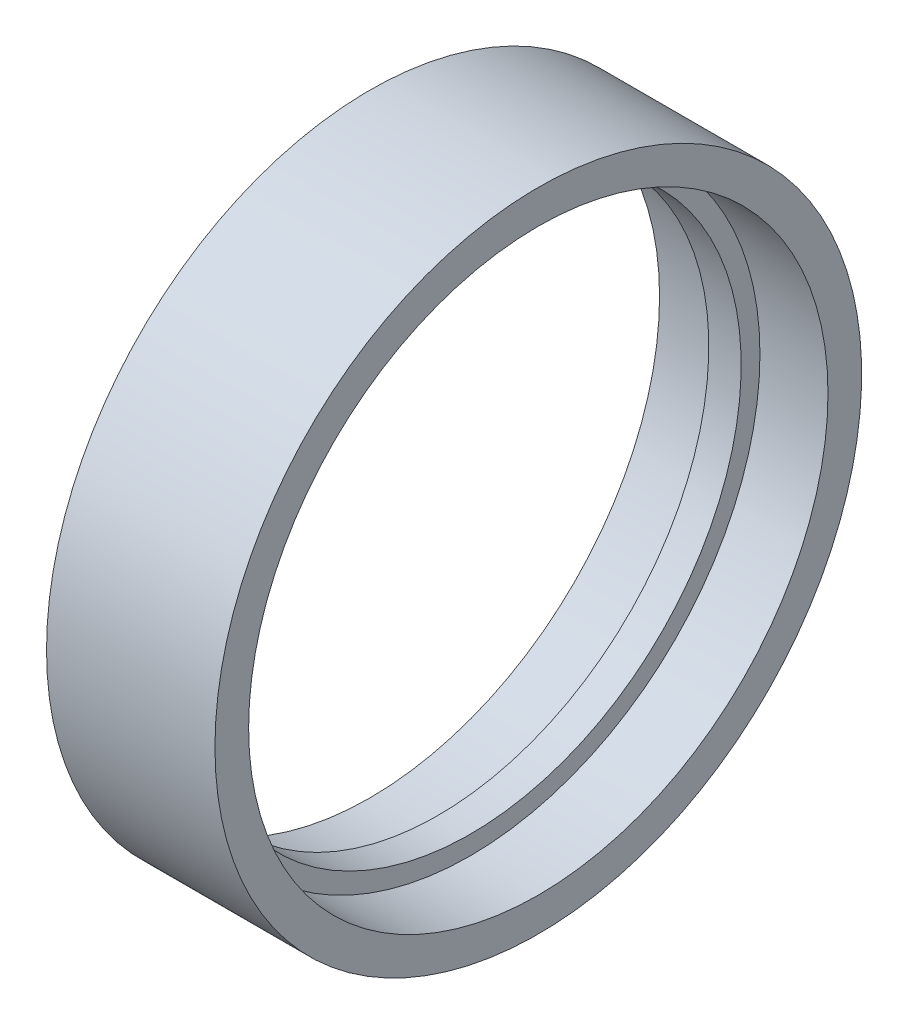
SolidWorks part; units mm, degrees
ref_plane "Ebene vorne" through (0, 0, 0) normal (0, 0, 1) x (1, 0, 0)
ref_plane "Ebene oben" through (0, 0, 0) normal (0, 1, 0) x (1, 0, 0)
ref_plane "Ebene rechts" through (0, 0, 0) normal (1, 0, 0) x (0, 0, -1)
sketch "Skizze1" plane through (0, 0, 0) normal (0, 0, 1) x (1, 0, 0)
  line L0 (-14.8859, 0) -> (39.3957, 0) construction
  line L1 (-12.5, 48) -> (12.5, 48)
  line L2 (-12.5, 48) -> (-12.5, 43)
  line L3 (-12.5, 43) -> (-2.4022, 43)
  line L4 (12.5, 48) -> (12.5, 43)
  line L6 (-2.4022, 43) -> (-2.4022, 40.2135)
  line L7 (-2.4022, 40.2135) -> (2.4022, 40.2135)
  line L8 (2.4022, 43) -> (2.4022, 40.2135)
  line L9 (0, 0) -> (0, 50.0688) construction
  line L10 (2.4022, 43) -> (12.5, 43)
  point P13 (0, 48)
  point P14 (0, 40.2135)
  dimension "D1" = 5
  dimension "20" = 25
  dimension "D2" = 48
revolve "Rotation1" add sketch "Skizze1" angle 360 about L0
